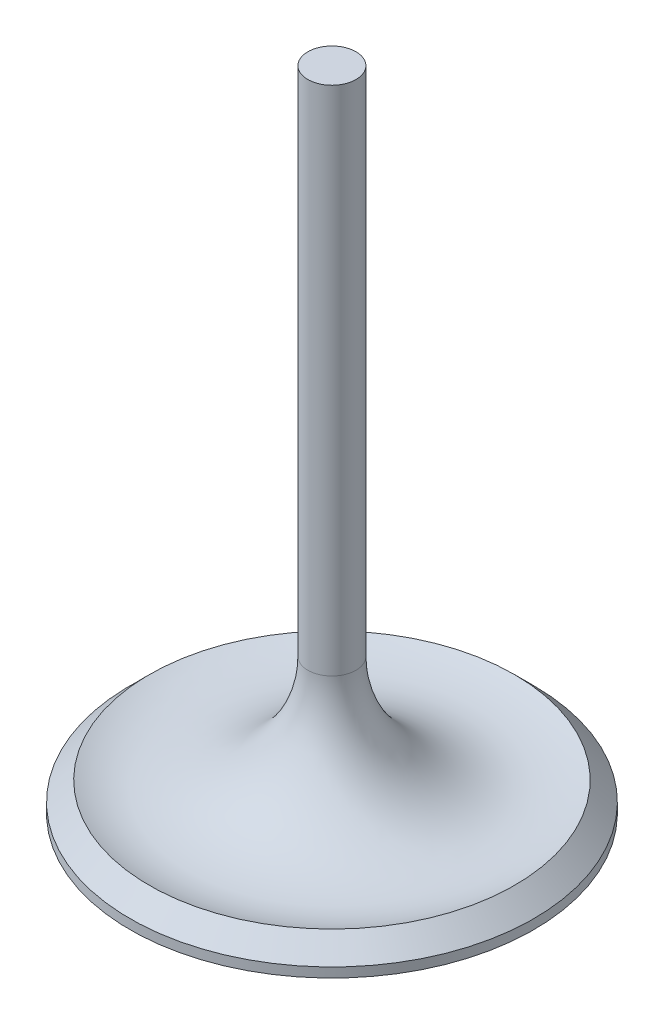
SolidWorks part; units mm, degrees
material "Alloy Steel"
ref_plane "Front Plane" through (0, 0, 0) normal (0, 0, 1) x (1, 0, 0)
ref_plane "Top Plane" through (0, 0, 0) normal (0, 1, 0) x (1, 0, 0)
ref_plane "Right Plane" through (0, 0, 0) normal (1, 0, 0) x (0, 0, -1)
sketch "Sketch1" plane through (0, 0, 0) normal (0, 0, 1) x (1, 0, 0)
  line L0 (0, 0) -> (0, 85.55)
  line L1 (0, 85.55) -> (3.18, 85.55)
  line L2 (3.18, 85.55) -> (3.18, 17.9547)
  line L3 (24.13, 3.81) -> (26.67, 1.27)
  line L4 (26.67, 1.27) -> (26.67, 0)
  line L5 (26.67, 0) -> (0, 0)
  arc A0 (3.18, 17.9547) -> (24.13, 3.81) centre (18.43, 17.9547) ccw
  dimension "D6" = 15.25
  dimension "D1" = 85.55
  dimension "D2" = 45
  dimension "D3" = 1.27
  dimension "D4" = 3.81
  dimension "D5" = 26.67
  dimension "D7" = 3.18
revolve "Revolve1" add sketch "Sketch1" angle 360 about L0
